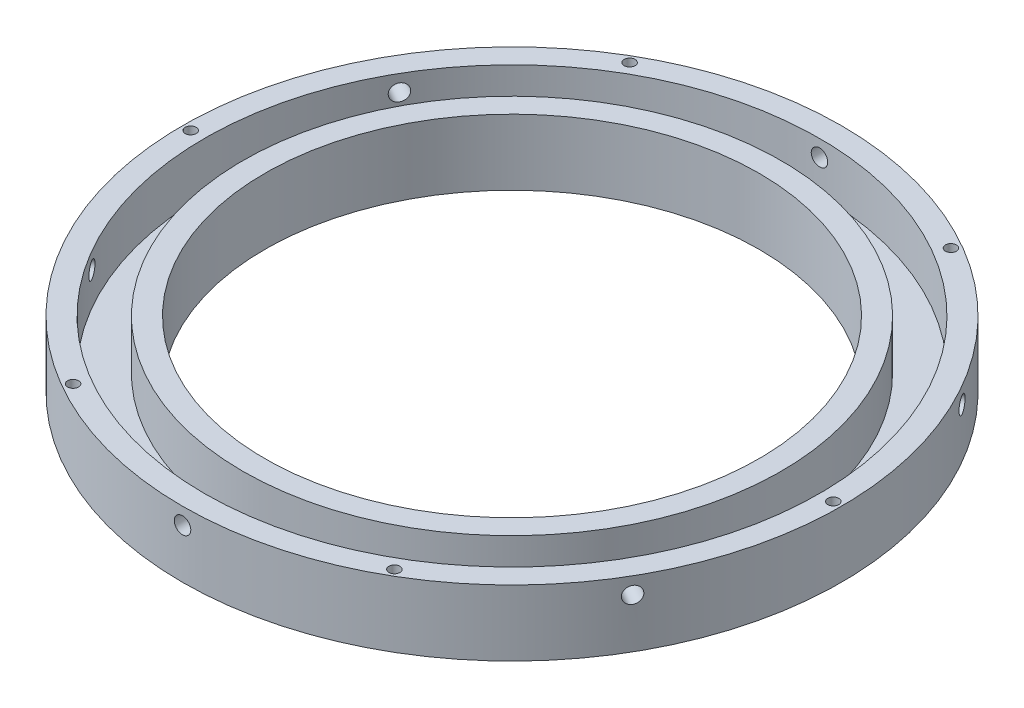
SolidWorks part; units mm, degrees
ref_plane "Front Plane" through (0, 0, 0) normal (0, 0, 1) x (1, 0, 0)
ref_plane "Top Plane" through (0, 0, 0) normal (0, 1, 0) x (1, 0, 0)
ref_plane "Right Plane" through (0, 0, 0) normal (1, 0, 0) x (0, 0, -1)
sketch "Sketch1" plane through (0, 0, 0) normal (0, 1, 0) x (1, 0, 0)
  circle A0 centre (0, 0) radius 76.2
  circle A1 centre (0, 0) radius 57.15
  dimension "D1" = 152.4
  dimension "D2" = 114.3
extrude "Boss-Extrude1" add sketch "Sketch1" along normal blind 15.24
sketch "Sketch2" plane through (0, 15.24, 0) normal (0, 1, 0) x (1, 0, 0)
  circle A0 centre (0, 0) radius 62.23
  circle A1 centre (0, 0) radius 71.12
  circle A2 centre (0, 0) radius 76.2 construction
  circle A3 centre (0, 0) radius 57.15 construction
  dimension "D1" = 5.08
  dimension "D2" = 5.08
extrude "Cut-Extrude1" cut sketch "Sketch2" against normal blind 11.43
sketch "Sketch3" plane through (0, 0, 0) normal (0, -1, 0) x (1, 0, 0)
  circle A0 centre (-66.675, 0) radius 4.318
  circle A1 centre (66.675, 0) radius 4.318
  dimension "D3" = 8.636
  dimension "D1" = 66.675
  dimension "D2" = 66.675
extrude "Cut-Extrude2" cut sketch "Sketch3" against normal up to next
sketch "Sketch4" plane through (0, 0, 0) normal (0, -1, 0) x (1, 0, 0)
  circle A0 centre (-66.675, 0) radius 6.858
  circle A1 centre (66.675, 0) radius 6.858
  circle A2 centre (-66.675, 0) radius 4.318 construction
  dimension "D1" = 2.54
extrude "Cut-Extrude3" cut sketch "Sketch4" against normal blind 1.27
ref_plane "Plane1" through (0, 0, 76.2) normal (0, 0, 1) x (1, 0, 0)
sketch "Sketch5" plane through (0, 0, 76.2) normal (0, 0, 1) x (1, 0, 0)
  line L0 (0, -8.382) -> (0, 8.382) construction
  line L1 (76.2, 15.24) -> (-76.2, 15.24) construction
  circle A0 centre (0, 11.43) radius 1.905
  dimension "D2" = 3.81
  dimension "D1" = 3.81
extrude "Cut-Extrude4" cut sketch "Sketch5" against normal up to next
pattern_circular "CirPattern1" count 6 over 360 about axis through (0, 15.24, 0) along (0, -1, 0) of "Cut-Extrude4"
sketch "Sketch6" plane through (0, 15.24, 0) normal (0, 1, 0) x (1, 0, 0)
  line L0 (0, 0) -> (37.1475, 64.3414) construction
  line L1 (-8.382, 0) -> (8.382, 0) construction
  circle A0 centre (37.1475, 64.3414) radius 1.27
  circle A1 centre (0, 0) radius 74.295 construction
  circle A2 centre (74.295, 0) radius 1.27
  circle A3 centre (37.1475, -64.3414) radius 1.27
  circle A4 centre (-37.1475, -64.3414) radius 1.27
  circle A5 centre (-74.295, 0) radius 1.27
  circle A6 centre (-37.1475, 64.3414) radius 1.27
  point P20 (0, 0)
  dimension "D1" = 2.54
  dimension "D3" = 148.59
  dimension "D2" = 60
  dimension "D4" = 6
extrude "Cut-Extrude5" cut sketch "Sketch6" against normal blind 2.54
equation "\"D2@Sketch3\"=\"D1@Sketch3\""
